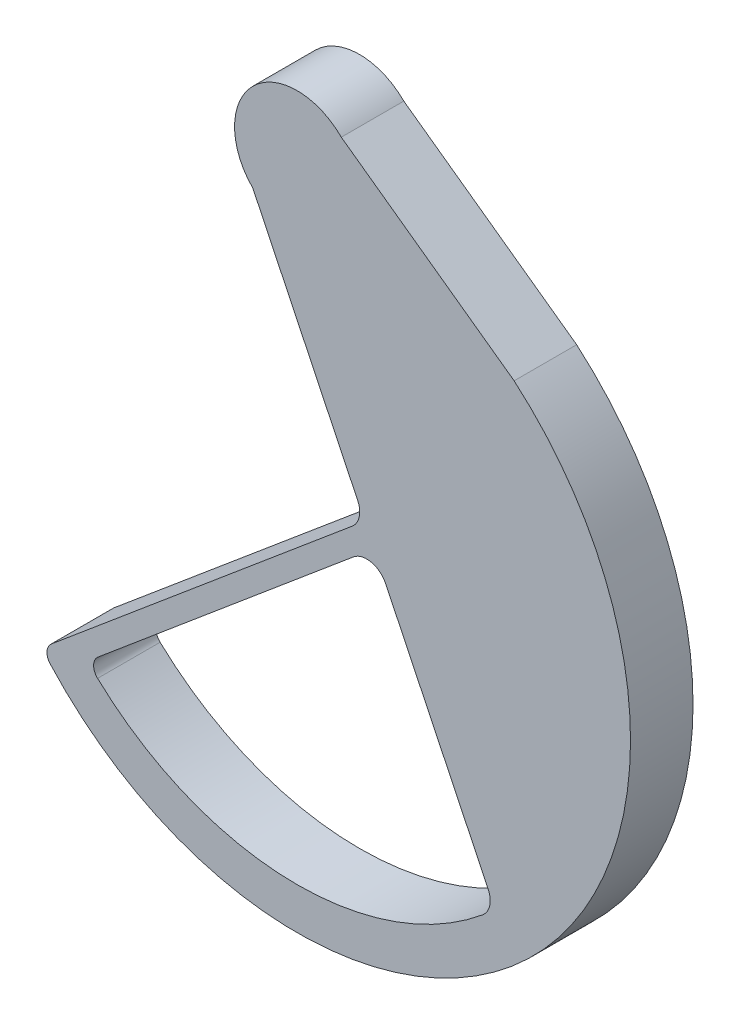
SolidWorks part; units mm, degrees
ref_plane "正面" through (0, 0, 0) normal (0, 0, 1) x (1, 0, 0)
ref_plane "平面" through (0, 0, 0) normal (0, 1, 0) x (1, 0, 0)
ref_plane "右側面" through (0, 0, 0) normal (1, 0, 0) x (0, 0, -1)
sketch "ｽｹｯﾁ4" plane through (0, 0, 0) normal (0, 0, 1) x (1, 0, 0)
  line L0 (0, 0.7897) -> (0, 0)
  line L1 (-53.6231, -124.9951) -> (-58.9406, -129.4571)
  line L3 (-10.6066, -10.6066) -> (14.5363, -62.8896)
  line L4 (-53.6231, -124.9951) -> (13.2442, -68.8868)
  line L5 (21.2324, -76.8138) -> (45.8448, -127.9938)
  line L6 (10.6066, 10.6066) -> (52.0762, -19.2705)
  line L7 (-58.0696, -135.2532) -> (-57.9498, -135.1527)
  line L8 (-47.7477, -126.5866) -> (13.5112, -75.1515)
  arc A1 (-59.2335, -133.7716) -> (52.0762, -19.2705) centre (0, -80) ccw
  arc A2 (-47.8702, -131.073) -> (44.5187, -134.0193) centre (0, -80) ccw
  arc A3 (10.6066, 10.6066) -> (-10.6066, -10.6066) centre (0, 0) ccw
  arc A4 (-59.2335, -133.7716) -> (-58.9406, -129.4571) centre (-57.0123, -131.7552) cw
  arc A5 (-47.8702, -131.073) -> (-47.7477, -126.5866) centre (-45.8186, -128.8841) cw
  arc A6 (13.5112, -75.1515) -> (21.2324, -76.8138) centre (16.7264, -78.9807) cw
  arc A7 (13.2442, -68.8868) -> (14.5363, -62.8896) centre (10.0302, -65.0566) ccw
  arc A8 (45.8448, -127.9938) -> (44.5187, -134.0193) centre (41.3388, -130.1608) cw
  point P18 (-61.2836, -131.423)
  point P21 (-50.2744, -128.7081)
  point P24 (18.4421, -71.0114)
  dimension "D3" = 140
  dimension "D4" = 30
  dimension "D5" = 5
  dimension "D6" = 3
  dimension "D7" = 3
  dimension "D8" = 5
  dimension "D9" = 5
  dimension "D10" = 5
  dimension "D2" = 5
extrude "ﾎﾞｽ - 押し出し1" add sketch "ｽｹｯﾁ4" along normal blind 15
sketch "ｽｹｯﾁ9" plane through (0, 0, 0) normal (0, 0, -1) x (-1, 0, 0)
  circle A0 centre (0, 0) radius 10.1
  dimension "D1" = 20.2
extrude "ｶｯﾄ - 押し出し3" cut sketch "ｽｹｯﾁ9" against normal blind 2
